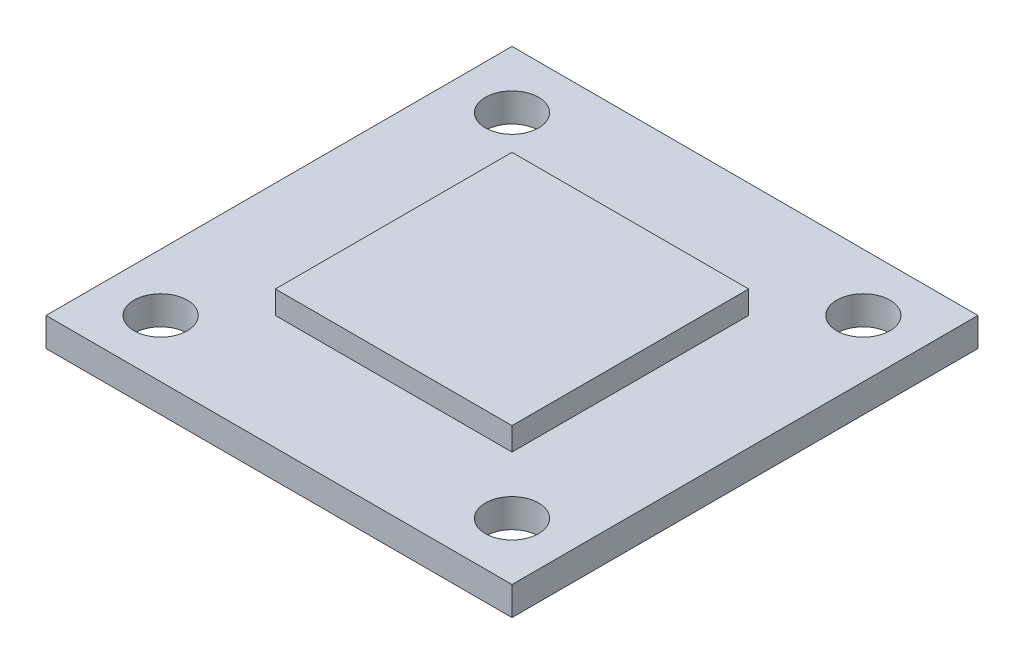
SolidWorks part; units mm, degrees
ref_plane "Front Plane" through (0, 0, 0) normal (0, 0, 1) x (1, 0, 0)
ref_plane "Top Plane" through (0, 0, 0) normal (0, 1, 0) x (1, 0, 0)
ref_plane "Right Plane" through (0, 0, 0) normal (1, 0, 0) x (0, 0, -1)
sketch "Sketch1" plane through (0, 0, 0) normal (0, 1, 0) x (1, 0, 0)
  line L1 (-12.9032, -12.9032) -> (12.9032, -12.9032)
  line L2 (-12.9032, -12.9032) -> (-12.9032, 12.9032)
  line L3 (-12.9032, 12.9032) -> (12.9032, 12.9032)
  line L4 (12.9032, -12.9032) -> (12.9032, 12.9032)
  line L5 (-12.9032, -12.9032) -> (12.9032, 12.9032) construction
  line L6 (-12.9032, 12.9032) -> (12.9032, -12.9032) construction
  point P0 (0, 0)
  dimension "D1" = 25.8064
  dimension "D2" = 25.8064
extrude "Boss-Extrude1" add sketch "Sketch1" along normal blind 1.5875
sketch "Sketch2" plane through (0, 1.5875, 0) normal (0, 1, 0) x (1, 0, 0)
  line L1 (-6.5532, -6.5532) -> (6.5532, -6.5532)
  line L2 (-6.5532, -6.5532) -> (-6.5532, 6.5532)
  line L3 (-6.5532, 6.5532) -> (6.5532, 6.5532)
  line L4 (6.5532, -6.5532) -> (6.5532, 6.5532)
  line L5 (-6.5532, -6.5532) -> (6.5532, 6.5532) construction
  line L6 (-6.5532, 6.5532) -> (6.5532, -6.5532) construction
  point P0 (0, 0)
  dimension "D1" = 13.1064
  dimension "D2" = 13.1064
extrude "Boss-Extrude2" add sketch "Sketch2" along normal blind 1.27
sketch "Sketch3" plane through (0, 1.5875, 0) normal (0, 1, 0) x (1, 0, 0)
  line L5 (-9.7282, -9.7282) -> (9.7282, 9.7282) construction
  line L6 (-9.7282, 9.7282) -> (9.7282, -9.7282) construction
  point P0 (0, 0)
  point P7 (-9.7282, 9.7282)
  point P8 (9.7282, 9.7282)
  point P9 (9.7282, -9.7282)
  point P10 (-9.7282, -9.7282)
  dimension "D1" = 19.4564
  dimension "D2" = 19.4564
hole_wizard "#32 (0.116) Diameter Hole1" positions "3DSketch1" profile "Sketch4" hole size "#32" standard "ANSI Inch" end condition through all
sketch3d "3DSketch1"
  point P0 (-9.7282, 1.5875, -9.7282)
  point P3 (-9.7282, 1.5875, 9.7282)
  point P6 (9.7282, 1.5875, 9.7282)
  point P9 (9.7282, 1.5875, -9.7282)
sketch "Sketch4" plane through (-9.7282, 1.5875, -9.7282) normal (1, 0, 0) x (0, 0, 1)
  line L0 (0, 0) -> (0, 1.5875)
  line L1 (0, 1.5875) -> (1.4732, 1.5875)
  line L2 (1.4732, 1.5875) -> (1.4732, 0)
  line L5 (1.4732, 0) -> (0, 0)
  line L11 (0, -6.35) -> (0, 107.95) construction
  dimension "Thru Hole Dia." = 2.9464
  dimension "Thru Hole Depth" = 1.5875
